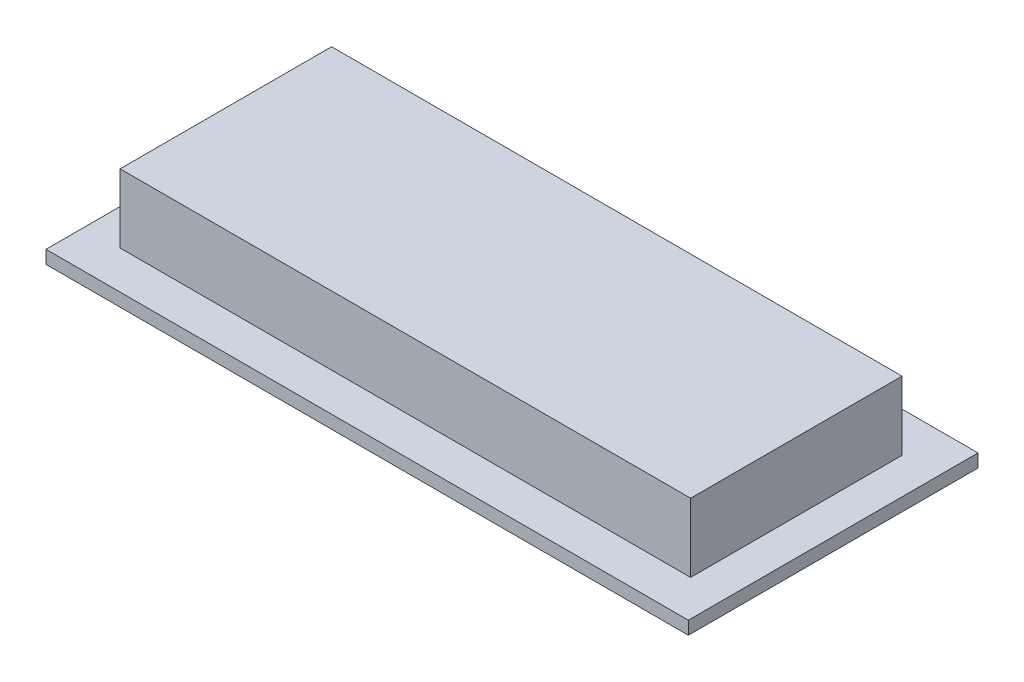
SolidWorks part; units mm, degrees
ref_plane "Front Plane" through (0, 0, 0) normal (0, 0, 1) x (1, 0, 0)
ref_plane "Top Plane" through (0, 0, 0) normal (0, 1, 0) x (1, 0, 0)
ref_plane "Right Plane" through (0, 0, 0) normal (1, 0, 0) x (0, 0, -1)
sketch "Sketch1" plane through (0, 0, 0) normal (0, 1, 0) x (1, 0, 0)
  line L1 (39.9669, -18.0213) -> (-39.9669, -18.0213)
  line L2 (39.9669, -18.0213) -> (39.9669, 18.0213)
  line L3 (39.9669, 18.0213) -> (-39.9669, 18.0213)
  line L4 (-39.9669, -18.0213) -> (-39.9669, 18.0213)
  line L5 (39.9669, -18.0213) -> (-39.9669, 18.0213) construction
  line L6 (39.9669, 18.0213) -> (-39.9669, -18.0213) construction
  point P0 (0, 0)
  dimension "D1" = 79.9338
  dimension "D2" = 36.0426
extrude "Boss-Extrude1" add sketch "Sketch1" along normal blind 1.6256
sketch "Sketch2" plane through (0, 1.6256, 0) normal (0, 1, 0) x (1, 0, 0)
  line L0 (39.9669, -18.0213) -> (39.9669, 18.0213) construction
  line L1 (35.4965, -13.2715) -> (-35.4965, -13.2715)
  line L2 (35.4965, -13.2715) -> (35.4965, 13.0429)
  line L3 (35.4965, 13.0429) -> (-35.4965, 13.0429)
  line L4 (-35.4965, -13.2715) -> (-35.4965, 13.0429)
  line L5 (-39.9669, -18.0213) -> (39.9669, -18.0213) construction
  line L6 (-39.9669, 18.0213) -> (-39.9669, -18.0213) construction
  line L7 (39.9669, 18.0213) -> (-39.9669, 18.0213) construction
  point P0 (0, 0)
  dimension "D1" = 4.4704
  dimension "D2" = 4.9784
  dimension "D3" = 4.7498
  dimension "D4" = 4.4704
extrude "Boss-Extrude2" add sketch "Sketch2" along normal blind 8.5344
sketch "Sketch3" plane through (0, 0, 0) normal (0, -1, 0) x (1, 0, 0)
  line L0 (-39.9669, -18.0213) -> (-39.9669, 18.0213) construction
  line L1 (-33.2359, -16.9799) -> (7.4041, -16.9799)
  line L2 (-33.2359, -16.9799) -> (-33.2359, -14.4399)
  line L3 (-33.2359, -14.4399) -> (7.4041, -14.4399)
  line L4 (7.4041, -16.9799) -> (7.4041, -14.4399)
  line L5 (39.9669, -18.0213) -> (-39.9669, -18.0213) construction
  dimension "D1" = 6.731
  dimension "D2" = 1.0414
  dimension "D3" = 40.64
  dimension "D4" = 2.54
extrude "Boss-Extrude3" add sketch "Sketch3" along normal blind 8.3312
